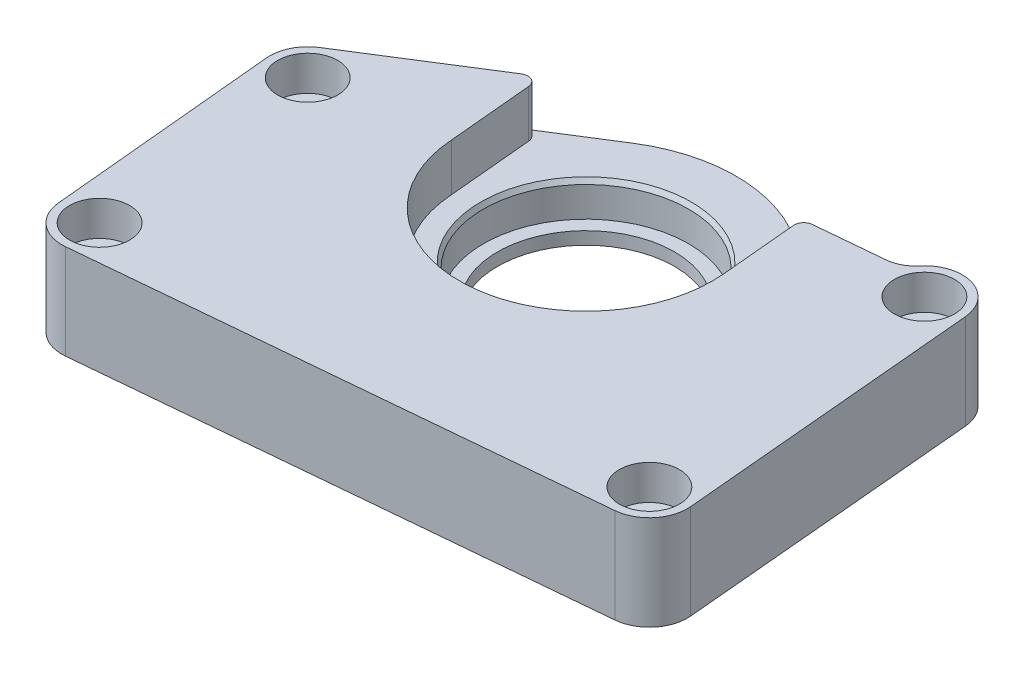
SolidWorks part; units mm, degrees
ref_plane "Front Plane" through (0, 0, 0) normal (0, 0, 1) x (1, 0, 0)
ref_plane "Top Plane" through (0, 0, 0) normal (0, 1, 0) x (1, 0, 0)
ref_plane "Right Plane" through (0, 0, 0) normal (1, 0, 0) x (0, 0, -1)
sketch "Sketch" plane through (0, 0, 0) normal (0, 1, 0) x (1, 0, 0)
  line L0 (-79.8657, -6.8827) -> (-73.0332, -79.5622) construction
  line L1 (-73.0332, -79.5622) -> (86.2969, -64.9372) construction
  line L2 (-79.8657, -6.8827) -> (77.7126, 30.6782) construction
  line L3 (77.7126, 30.6782) -> (86.2969, -64.9372) construction
  line L4 (-79.8657, -6.8827) -> (86.2969, -64.9372) construction
  line L5 (-0.1322, 1.4405) -> (6.6319, -72.2497) construction
  line L6 (67.1396, -30.4868) -> (83.0755, -29.056) construction
  line L7 (-54.5149, -62.8628) -> (-74.4271, -64.7347) construction
  line L8 (77.7126, 36.1782) -> (30.7635, 31.8688) construction
  circle A0 centre (-0.1322, 1.4405) radius 28
  circle A1 centre (-0.1322, 1.4405) radius 43.3639
  circle A3 centre (86.2969, -64.9372) radius 5.5
  circle A4 centre (86.2969, -64.9372) radius 12
  circle A6 centre (-73.0332, -79.5622) radius 5.5
  arc A7 (-76.6706, -68.1267) -> (-62.0333, -84.3583) centre (-73.0332, -79.5622) ccw
  circle A11 centre (77.7126, 30.6782) radius 5.5
  circle A12 centre (77.7126, 30.6782) radius 12
  circle A15 centre (-79.8657, -6.8827) radius 5.5
  circle A16 centre (-79.8657, -6.8827) radius 12
  arc A19 (-56.8302, -81.3952) -> (-73.1872, -63.2566) centre (-54.5149, -62.8628) ccw
  circle A20 centre (-54.5149, -62.8628) radius 10
  arc A21 (-62.0333, -84.3583) -> (-56.8302, -81.3952) centre (-57.4501, -86.3566) cw
  arc A22 (-76.6706, -68.1267) -> (-73.1872, -63.2566) centre (-78.1861, -63.362) ccw
  circle A25 centre (67.1396, -30.4868) radius 7.5
  circle A26 centre (67.1396, -30.4868) radius 14
  dimension "D1" = 5
sketch "fit test sketch" plane through (0, 0, 0) normal (0, 1, 0) x (1, 0, 0)
  line L0 (35.8764, 25.8461) -> (65.9418, 33.0126)
  line L1 (40.606, 16.6933) -> (68.2605, 23.2851)
  line L5 (78.87, -38.1287) -> (80.3415, -54.5193)
  line L8 (4.8411, -41.7742) -> (62.9107, -62.0628)
  line L9 (20.7273, -36.7318) -> (77.6478, -56.6189)
  line L15 (73.7081, 19.3661) -> (77.3212, -20.8776)
  line L16 (83.668, 20.2603) -> (90.3015, -53.6251)
  line L17 (-46.6578, -46.1708) -> (-31.7565, -28.9876)
  line L18 (-39.1029, -52.7225) -> (-23.7895, -35.0641)
  line L21 (-61.7132, -83.5442) -> (75.8909, -70.9134)
  line L23 (-38.1277, -71.3372) -> (62.9107, -62.0628)
  line L24 (-62.109, -7.7902) -> (-40.225, -15.4361)
  line L25 (-62.109, -7.7902) -> (-43.3706, -3.3236)
  line L26 (-73.8667, -17.2755) -> (-70.4544, -53.5734)
  line L27 (-71.2166, -15.2009) -> (-31.7565, -28.9876)
  line L28 (-83.8228, -18.2115) -> (-79.0323, -69.1694)
  line L34 (-70.4136, 0.5104) -> (-43.2783, 6.9785)
  circle A0 centre (-0.1322, 1.4405) radius 28
  arc A1 (-23.7895, -35.0641) -> (4.8411, -41.7742) centre (-0.1322, 1.4405) ccw
  circle A2 centre (-79.8657, -6.8827) radius 5.5
  arc A3 (-70.4136, 0.5104) -> (-83.8228, -18.2115) centre (-79.8657, -6.8827) ccw
  circle A4 centre (-54.5149, -62.8628) radius 10
  arc A5 (-46.6578, -46.1708) -> (-70.4544, -53.5734) centre (-54.5149, -62.8628) ccw
  circle A6 centre (-73.0332, -79.5622) radius 5.5
  arc A7 (-79.0323, -69.1694) -> (-61.7132, -83.5442) centre (-73.0332, -79.5622) ccw
  circle A8 centre (86.2969, -64.9372) radius 5.5
  arc A9 (75.8909, -70.9134) -> (90.3015, -53.6251) centre (86.2969, -64.9372) ccw
  arc A10 (77.3212, -20.8776) -> (78.87, -38.1287) centre (67.1396, -30.4868) ccw
  circle A11 centre (67.1396, -30.4868) radius 7.5
  circle A12 centre (77.7126, 30.6782) radius 5.5
  arc A13 (68.2605, 23.2851) -> (73.7081, 19.3661) centre (77.7126, 30.6782) ccw
  arc A14 (-43.3706, -3.3236) -> (-40.225, -15.4361) centre (-0.1322, 1.4405) ccw
  arc A15 (35.8764, 25.8461) -> (-43.2783, 6.9785) centre (-0.1322, 1.4405) ccw
  arc A16 (20.7273, -36.7318) -> (40.606, 16.6933) centre (-0.1322, 1.4405) ccw
  arc A18 (-38.1277, -71.3372) -> (-39.1029, -52.7225) centre (-54.5149, -62.8628) ccw
  arc A19 (-73.8667, -17.2755) -> (-71.2166, -15.2009) centre (-79.8657, -6.8827) ccw
  arc A20 (80.3415, -54.5193) -> (77.6478, -56.6189) centre (86.2969, -64.9372) ccw
  arc A21 (83.668, 20.2603) -> (65.9418, 33.0126) centre (77.7126, 30.6782) ccw
sketch "Sketch7" plane through (0, 0, 0) normal (0, 1, 0) x (1, 0, 0)
  line L0 (-91.8131, -8.0058) -> (-84.9806, -80.6854)
  line L1 (-86.268, 3.2668) -> (-25.4745, 41.6153)
  line L2 (40.7826, 32.7884) -> (61.6421, 34.7031)
  line L3 (77.7126, 36.1782) -> (30.7635, 31.8688) construction
  line L4 (89.6645, 31.7513) -> (98.2489, -63.8641)
  line L5 (87.3938, -76.8869) -> (-71.9364, -91.512)
  circle A0 centre (77.7126, 30.6782) radius 5.5
  arc A1 (89.6645, 31.7513) -> (68.4483, 38.3053) centre (77.7126, 30.6782) ccw
  circle A2 centre (-79.8657, -6.8827) radius 5.5
  arc A3 (-86.268, 3.2668) -> (-91.8131, -8.0058) centre (-79.8657, -6.8827) ccw
  arc A4 (-84.9806, -80.6854) -> (-71.9364, -91.512) centre (-73.0332, -79.5622) ccw
  circle A6 centre (86.2969, -64.9372) radius 5.5
  arc A7 (87.3938, -76.8869) -> (98.2489, -63.8641) centre (86.2969, -64.9372) ccw
  arc A9 (32.9119, 35.5629) -> (-25.4745, 41.6153) centre (-0.1322, 1.4405) ccw
  circle A10 centre (-73.0332, -79.5622) radius 5.5
  arc A11 (61.6421, 34.7031) -> (68.4483, 38.3053) centre (60.728, 44.6613) ccw
  arc A12 (40.7826, 32.7884) -> (32.9119, 35.5629) centre (39.8685, 42.7465) cw
  circle A14 centre (-0.1322, 1.4405) radius 28
  point P17 (66.5794, 35.1563)
extrude "Main body" add sketch "Sketch7" along normal blind 30 separate body
sketch "bolt head countersink" plane through (0, 30, 0) normal (0, 1, 0) x (1, 0, 0)
  circle A0 centre (-79.8657, -6.8827) radius 9.5
  circle A1 centre (-73.0332, -79.5622) radius 9.5
  circle A2 centre (77.7126, 30.6782) radius 9.5
  circle A3 centre (86.2969, -64.9372) radius 9.5
extrude "countersink holes" cut sketch "bolt head countersink" against normal blind 11
sketch "Sketch9" plane through (0, 30, 0) normal (0, 1, 0) x (1, 0, 0)
  circle A0 centre (-0.1322, 1.4405) radius 32.45
extrude "Cut-Extrude2" cut sketch "Sketch9" against normal blind 26
sketch "Sketch10" plane through (0, 30, 0) normal (0, 1, 0) x (1, 0, 0)
  line L0 (0, 0) -> (-6.3985, 69.707) construction
  line L1 (-6.3985, 69.707) -> (33.4341, 73.3632) construction
  line L2 (-6.3985, 69.707) -> (-46.231, 66.0507) construction
  line L3 (-46.231, 66.0507) -> (-40.0392, -1.2863)
  line L4 (33.4341, 73.3632) -> (39.7003, 5.0968)
  line L5 (-46.231, 66.0507) -> (33.4341, 73.3632)
  arc A0 (-40.0392, -1.2863) -> (39.7003, 5.0968) centre (-0.1322, 1.4405) ccw
  point P2 (0, 0)
  point P6 (0, 0)
  point P12 (0, 0)
extrude "Cut-Extrude3" cut sketch "Sketch10" against normal blind 15
fillet "round edges" radius 3 2 edges at (37.1272, 22.5, -33.1296) (-42.9693, 22.5, -30.5796)
chamfer "30 Chamfer1" distance 1.5 angle 30 1 edges at (-0.1322, 15, 31.0095)
sketch "Sketch11" plane through (0, 0, 0) normal (0, -1, 0) x (1, 0, 0)
  circle A0 centre (-0.1322, -1.4405) radius 44.5
  circle A1 centre (-0.1322, -1.4405) radius 38.5
  circle A2 centre (-54.5149, 62.8628) radius 17.5
  circle A3 centre (-54.5149, 62.8628) radius 11.5
  circle A4 centre (67.1396, 30.4868) radius 8
  circle A5 centre (67.1396, 30.4868) radius 14
extrude "Cut-Extrude4" cut sketch "Sketch11" against normal blind 3
